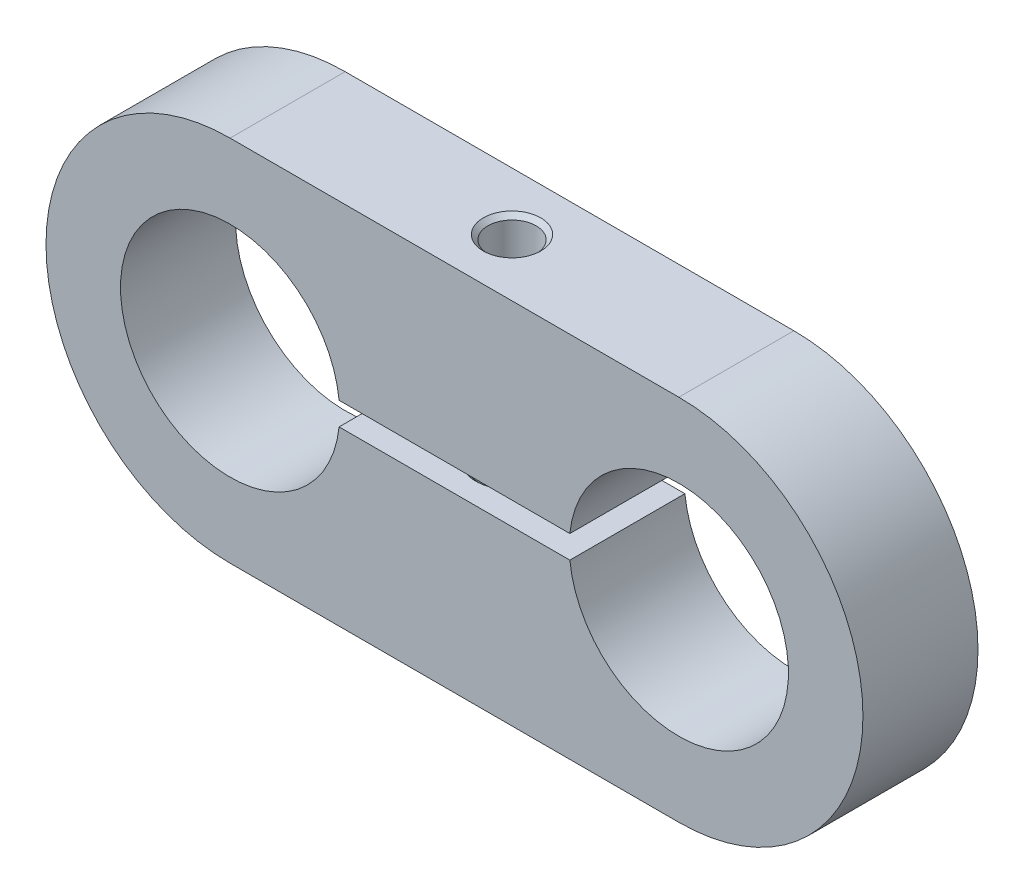
SolidWorks part; units mm, degrees
ref_plane "Front Plane" through (0, 0, 0) normal (0, 0, 1) x (1, 0, 0)
ref_plane "Top Plane" through (0, 0, 0) normal (0, 1, 0) x (1, 0, 0)
ref_plane "Right Plane" through (0, 0, 0) normal (1, 0, 0) x (0, 0, -1)
ref_plane "Plane4" through (0, 0, 0) normal (0, 0, -1) x (-1, 0, 0)
sketch "Sketch1" plane through (0, 0, 0) normal (0, 0, -1) x (-1, 0, 0)
  line L0 (0, 16) -> (-39, 16)
  line L1 (-39, -16) -> (0, -16)
  arc A0 (0, -16) -> (0, 16) centre (0, 0) ccw
  arc A1 (-39, 16) -> (-39, -16) centre (-39, 0) ccw
extrude "Boss-Extrude1" add sketch "Sketch1" against normal blind 10
sketch "Sketch2" plane through (0, 0, 10) normal (0, 0, 1) x (1, 0, 0)
  line L0 (28.0455, 1) -> (10.9545, 1)
  line L1 (10.9545, -1) -> (28.0455, -1)
  arc A0 (28.0455, -1) -> (28.0455, 1) centre (39, 0) cw
  arc A1 (10.9545, 1) -> (10.9545, -1) centre (0, 0) cw
extrude "Cut-Extrude1" cut sketch "Sketch2" against normal through all
ref_plane "Plane5" through (0, 0, 0) normal (0, -1, 0) x (1, 0, 0)
sketch "Sketch3" plane through (0, 0, 0) normal (0, -1, 0) x (1, 0, 0)
  line L0 (50, 10) -> (39, 10)
  line L1 (39, 10) -> (39, 0)
  line L2 (39, 0) -> (50, 0)
  line L3 (50, 0) -> (50, 10)
  line L4 (39, 10) -> (39, 0) construction
revolve "Cut-Revolve1" cut sketch "Sketch3" angle 360 about L4
sketch "Sketch4" plane through (0, 0, 0) normal (0, -1, 0) x (1, 0, 0)
  line L0 (11, 10) -> (0, 10)
  line L1 (0, 10) -> (0, 0)
  line L2 (0, 0) -> (11, 0)
  line L3 (11, 0) -> (11, 10)
  line L4 (0, 10) -> (0, 0) construction
revolve "Cut-Revolve2" cut sketch "Sketch4" angle 360 about L4
hole_wizard "#10 Clearance Hole1" positions "Sketch6" profile "Sketch5" hole size "#10" standard "ANSI Inch"
sketch "Sketch6" plane through (0, -16, 0) normal (0, -1, 0) x (-1, 0, 0)
  point P0 (-19.5, -5)
sketch "Sketch5" plane through (19.5, -16, 5) normal (1, 0, 0) x (0, 0, -1)
  line L0 (0, 0) -> (0, 15)
  line L1 (0, 15) -> (2.75, 15)
  line L2 (2.75, 15) -> (2.75, 0)
  line L5 (2.75, 0) -> (0, 0)
  line L11 (0, -6.35) -> (0, 107.95) construction
  dimension "Thru Hole Dia." = 5.5
  dimension "Thru Hole Depth" = 15
hole_wizard "#6 Clearance Hole1" positions "Sketch8" profile "Sketch7" hole size "#6" standard "ANSI Inch"
sketch "Sketch8" plane through (0, 16, 0) normal (0, 1, 0) x (1, 0, 0)
  point P0 (19.5, -5)
sketch "Sketch7" plane through (19.5, 16, 5) normal (1, 0, 0) x (0, 0, 1)
  line L0 (0, 0) -> (0, 32)
  line L1 (0, 32) -> (2.1, 32)
  line L2 (2.1, 32) -> (2.1, 0)
  line L5 (2.1, 0) -> (0, 0)
  line L11 (0, -6.35) -> (0, 107.95) construction
  dimension "Thru Hole Dia." = 4.2
  dimension "Thru Hole Depth" = 32
chamfer "Chamfer1" distance 0.4 angle 45 4 edges at (19.5, -1, 2.25) (19.5, 1, 7.1) (19.5, 16, 7.1) (19.5, -16, 2.25)
sketch "Sketch9" plane through (0, 0, 10) normal (0, 0, 1) x (1, 0, 0)
  line L0 (10.9545, 1) -> (9.4724, 1)
  line L1 (10.9545, -1) -> (9.4724, -1)
  line L2 (28.0455, -1) -> (29.5276, -1)
  line L3 (28.0455, 1) -> (29.5276, 1)
  arc A0 (9.4724, 1) -> (9.4724, -1) centre (0, 0) ccw
  arc A1 (10.9545, 1) -> (10.9545, -1) centre (0, 0) ccw
  arc A2 (29.5276, 1) -> (29.5276, -1) centre (39, 0) cw
  arc A3 (28.0455, 1) -> (28.0455, -1) centre (39, 0) cw
extrude "Boss-Extrude2" add sketch "Sketch9" against normal blind 10
